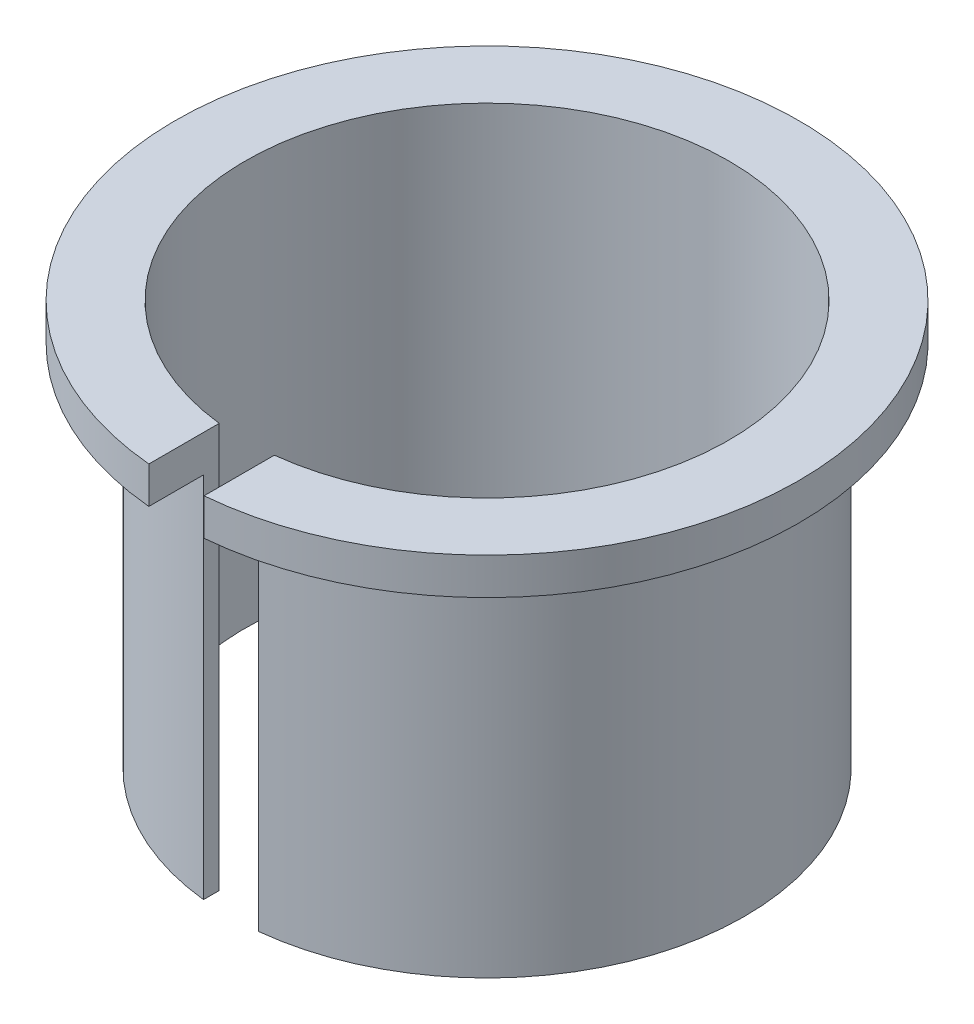
SolidWorks part; units mm, degrees
ref_plane "Front Plane" through (0, 0, 0) normal (0, 0, 1) x (1, 0, 0)
ref_plane "Top Plane" through (0, 0, 0) normal (0, 1, 0) x (1, 0, 0)
ref_plane "Right Plane" through (0, 0, 0) normal (1, 0, 0) x (0, 0, -1)
sketch "Sketch1" plane through (0, 0, 0) normal (0, 1, 0) x (1, 0, 0)
  line L2 (-1.5, -13.0642) -> (-1.5, -13.9194)
  line L4 (1.5, -13.0642) -> (1.5, -13.9194)
  arc A2 (1.5, -13.9194) -> (-1.5, -13.9194) centre (0, 0) ccw
  arc A3 (1.5, -13.0642) -> (-1.5, -13.0642) centre (0, 0) ccw
  point P4 (0, -14.7881)
  dimension "D3" = 3
  dimension "D4" = 0
extrude "Boss-Extrude1" add sketch "Sketch1" along normal blind 20
sketch "Sketch2" plane through (0, 20, 0) normal (0, 1, 0) x (1, 0, 0)
  line L0 (-1.5, -13.0642) -> (-1.5, -16.8884)
  line L1 (1.5, -13.0642) -> (1.5, -16.8884)
  arc A0 (1.5, -16.8884) -> (-1.5, -16.8884) centre (0, 0) ccw
  arc A1 (1.5, -13.0642) -> (-1.5, -13.0642) centre (0, 0) ccw
extrude "Boss-Extrude2" add sketch "Sketch2" along normal blind 2
